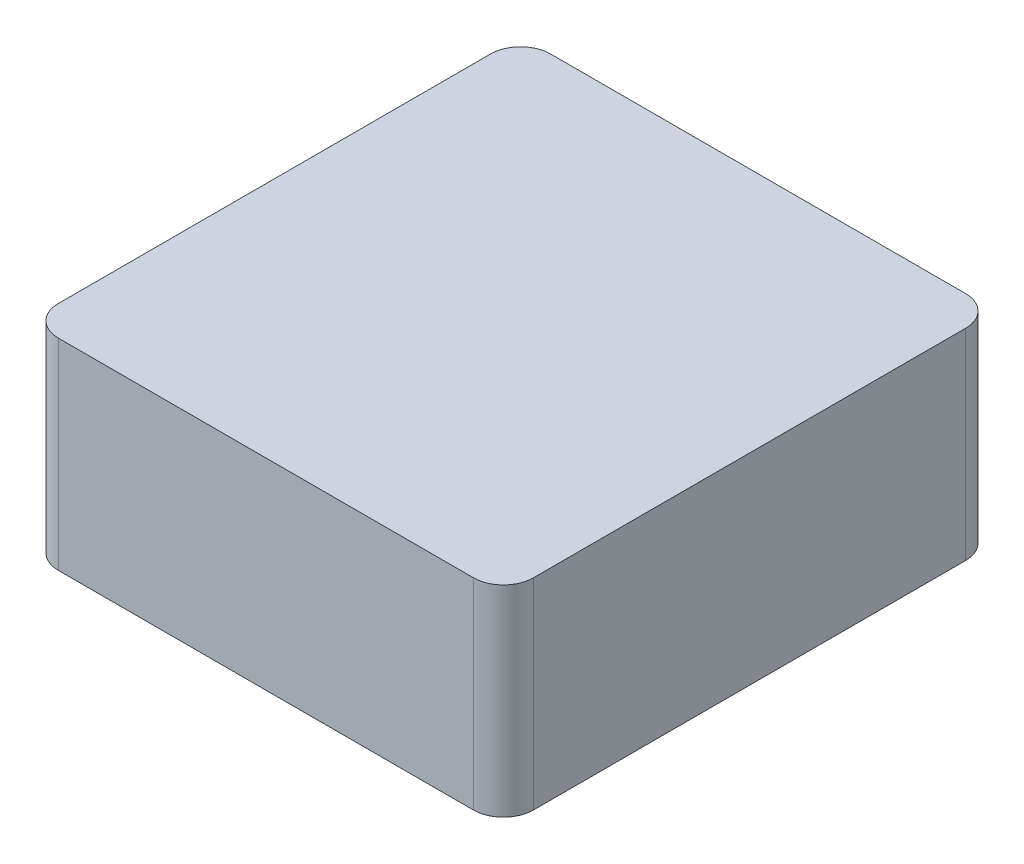
SolidWorks part; units mm, degrees
ref_plane "Front Plane" through (0, 0, 0) normal (0, 0, 1) x (1, 0, 0)
ref_plane "Top Plane" through (0, 0, 0) normal (0, 1, 0) x (1, 0, 0)
ref_plane "Right Plane" through (0, 0, 0) normal (1, 0, 0) x (0, 0, -1)
sketch "Sketch3" plane through (0, 0, 0) normal (0, 1, 0) x (1, 0, 0)
  line L1 (-48.5, 57.5) -> (48.5, 57.5)
  line L2 (-55.5, 50.5) -> (-55.5, -50.5)
  line L3 (-48.5, -57.5) -> (48.5, -57.5)
  line L4 (55.5, 50.5) -> (55.5, -50.5)
  line L5 (-55.5, 57.5) -> (55.5, -57.5) construction
  line L6 (-55.5, -57.5) -> (55.5, 57.5) construction
  arc A0 (48.5, -57.5) -> (55.5, -50.5) centre (48.5, -50.5) ccw
  arc A1 (-55.5, -50.5) -> (-48.5, -57.5) centre (-48.5, -50.5) ccw
  arc A2 (48.5, 57.5) -> (55.5, 50.5) centre (48.5, 50.5) cw
  arc A3 (-48.5, 57.5) -> (-55.5, 50.5) centre (-48.5, 50.5) ccw
  point P0 (0, 0)
  dimension "D2" = 7
  dimension "D1" = 111
  dimension "D3" = 115
extrude "Boss-Extrude1" add sketch "Sketch3" along normal mid plane 47
sketch "Sketch4" plane through (0, -23.5, 0) normal (0, -1, 0) x (1, 0, 0)
  line L0 (45, 47.5) -> (-45, 47.5) construction
  line L1 (45, -47.5) -> (45, 47.5) construction
  circle A0 centre (45, 47.5) radius 6
  circle A1 centre (-45, 47.5) radius 6
  circle A2 centre (-45, -47.5) radius 6
  circle A3 centre (45, -47.5) radius 6
  point P8 (45, 0)
  point P9 (0, 47.5)
  dimension "D1" = 90
  dimension "D2" = 12
  dimension "D3" = 95
extrude "Boss-Extrude2" add sketch "Sketch4" along normal blind 3.25
hole_wizard "M3x0.5 Tapped Hole1" positions "Sketch5" profile "Sketch6" tap size "M3x0.5" standard "ANSI Metric"
sketch "Sketch5" plane through (0, -23.5, 0) normal (0, -1, 0) x (-1, 0, 0)
  line L0 (-42.5, 0) -> (42.5, 0) construction
  point P0 (-42.5, 0)
  point P2 (42.5, 0)
  dimension "D1" = 85
sketch "Sketch6" plane through (42.5, -23.5, 0) normal (1, 0, 0) x (0, 0, -1)
  line L0 (0, 0) -> (0, 5.2511)
  line L1 (0, 5.2511) -> (1.25, 4.5)
  line L2 (1.25, 4.5) -> (1.25, 0)
  line L5 (1.25, 0) -> (0, 0)
  line L10 (0, 5.2511) -> (-1.25, 4.5) construction
  line L11 (0, -6.35) -> (0, 107.95) construction
  dimension "Tap Drill Dia." = 2.5
  dimension "Tap Drill Depth" = 4.5
  dimension "Drill Angle" = 118
cosmetic thread "Hole Thread1" parameters "D1"=6, "D2"=3
cosmetic thread "Hole Thread2" parameters "D1"=6, "D2"=3
